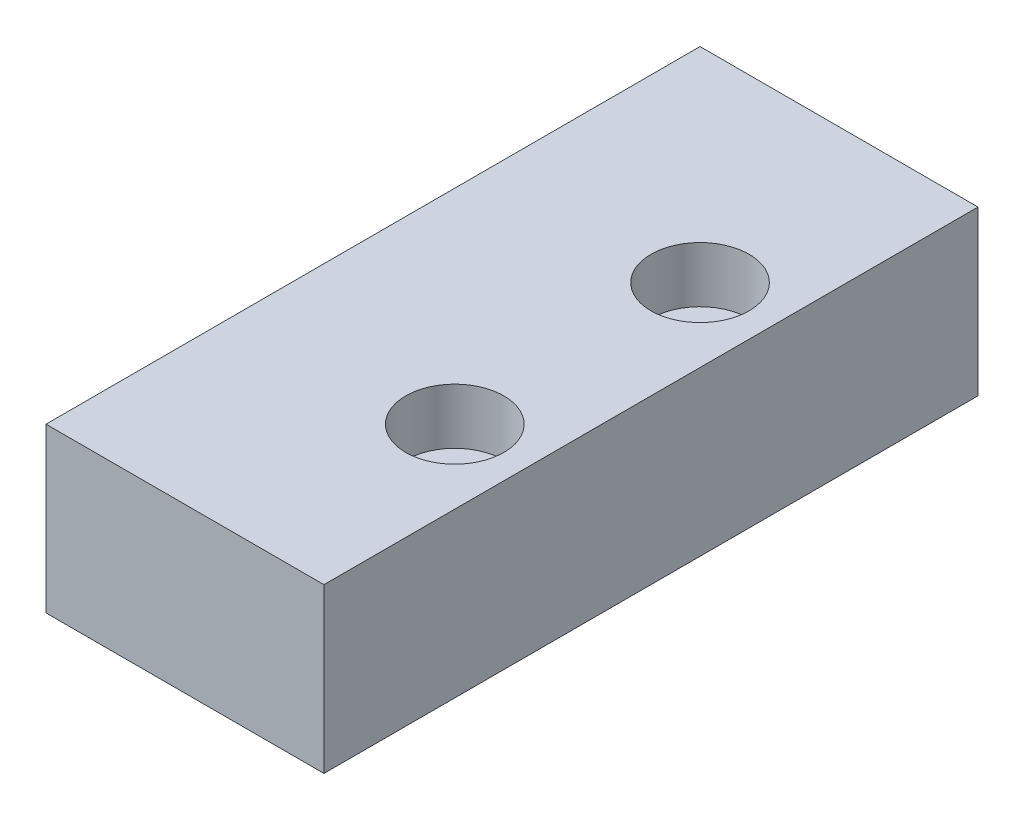
SolidWorks part; units mm, degrees
ref_plane "Front" through (0, 0, 0) normal (0, 0, 1) x (1, 0, 0)
ref_plane "Top" through (0, 0, 0) normal (0, 1, 0) x (1, 0, 0)
ref_plane "Right" through (0, 0, 0) normal (1, 0, 0) x (0, 0, -1)
sketch "草图1" plane through (0, 0, 0) normal (0, 1, 0) x (1, 0, 0)
  line L0 (0, 0) -> (0, 20)
  line L1 (0, 20) -> (-17, 20)
  line L2 (-17, 20) -> (-17, -20)
  line L3 (-17, -20) -> (0, -20)
  line L4 (0, -20) -> (0, 0)
  dimension "D1" = 20
  dimension "D2" = 17
extrude "凸台-拉伸1" add sketch "草图1" along normal blind 10
sketch "草图2" plane through (0, 10, 0) normal (0, 1, 0) x (1, 0, 0)
  line L0 (-24.8594, 0) -> (9.0488, 0) construction
  line L1 (-4.5, 21.0242) -> (-4.5, -21.2488) construction
  line L2 (0, -20) -> (0, 20) construction
  point P7 (-4.5, 7.5)
  point P8 (-4.5, -7.5)
  dimension "D1" = 4.5
  dimension "D2" = 7.5
hole_wizard "打孔尺寸(%根据)内六角圆柱头螺钉的类型1" positions "3D草图1" profile "草图3" counterbore size "M3" standard "GB" end condition through all
sketch3d "3D草图1"
  point P0 (-4.5, 10, -7.5)
  point P3 (-4.5, 10, 7.5)
sketch "草图3" plane through (-4.5, 10, -7.5) normal (1, 0, 0) x (0, 0, 1)
  line L0 (0, 0) -> (0, 10)
  line L1 (0, 10) -> (1.7, 10)
  line L3 (1.7, 10) -> (1.7, 3.4)
  line L4 (1.7, 3.4) -> (3, 3.4)
  line L5 (3, 3.4) -> (3, 0)
  line L7 (3, 0) -> (0, 0)
  line L11 (0, -6.35) -> (0, 107.95) construction
  dimension "通孔孔直径" = 3.4
  dimension "通孔孔深度" = 10
  dimension "柱形沉头孔直径" = 6
  dimension "柱形沉头孔深度" = 3.4
sketch "草图4" plane through (-17, 0, 0) normal (-1, 0, 0) x (0, 0, 1)
  line L0 (0, 14.1316) -> (0, -3.5676) construction
  line L1 (-24.0978, 5) -> (22.4076, 5) construction
  line L3 (-20, 0) -> (20, 0) construction
  point P7 (-12, 5)
  point P8 (12, 5)
  point P9 (0, 5)
  dimension "D1" = 5
  dimension "D2" = 12
hole_wizard "M3 螺纹孔2" positions "3D草图4" profile "草图7" tap size "M3" standard "GB"
sketch3d "3D草图4"
  point P0 (-17, 5, -12)
  point P3 (-17, 5, 0)
  point P6 (-17, 5, 12)
sketch "草图7" plane through (-17, 5, -12) normal (0, 1, 0) x (0, 0, 1)
  line L0 (0, 0) -> (0, 8.2511)
  line L1 (0, 8.2511) -> (1.25, 7.5)
  line L2 (1.25, 7.5) -> (1.25, 0)
  line L5 (1.25, 0) -> (0, 0)
  line L10 (0, 8.2511) -> (-1.25, 7.5) construction
  line L11 (0, -6.35) -> (0, 107.95) construction
  dimension "螺纹孔钻头直径" = 2.5
  dimension "螺纹孔钻头深度" = 7.5
  dimension "导头角度" = 118
cosmetic thread "孔螺蚊线4" parameters "D1"=6, "D2"=3
cosmetic thread "孔螺蚊线5" parameters "D1"=6, "D2"=3
cosmetic thread "孔螺蚊线6" parameters "D1"=6, "D2"=3
